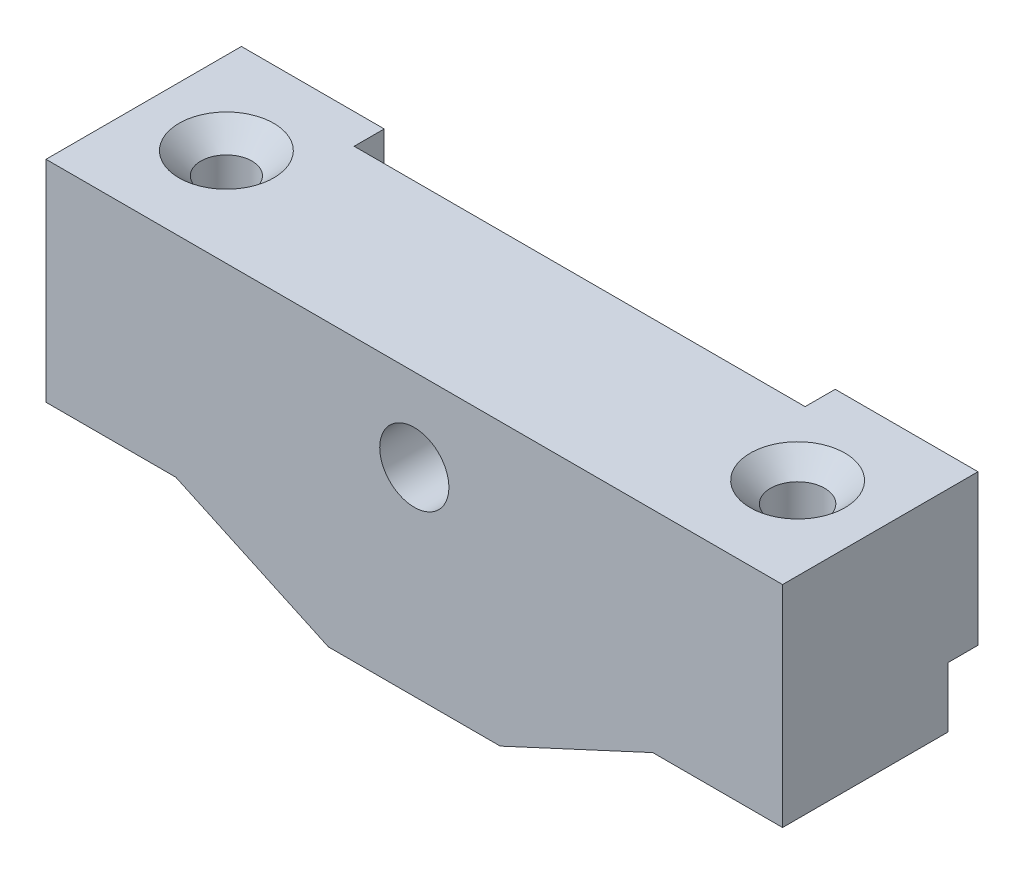
SolidWorks part; units mm, degrees
ref_plane "Front Plane" through (0, 0, 0) normal (0, 0, 1) x (1, 0, 0)
ref_plane "Top Plane" through (0, 0, 0) normal (0, 1, 0) x (1, 0, 0)
ref_plane "Right Plane" through (0, 0, 0) normal (1, 0, 0) x (0, 0, -1)
sketch "Sketch2" plane through (0, 0, 0) normal (0, 0, 1) x (1, 0, 0)
  line L0 (12.9822, 18.1755) -> (23.9822, 18.1755)
  line L1 (23.9822, 18.1755) -> (42.9822, 26.9755)
  line L2 (42.9822, 26.9755) -> (42.9822, 36.9755)
  line L3 (42.9822, 36.9755) -> (-6.0178, 36.9755)
  line L4 (-6.0178, 36.9755) -> (-6.0178, 26.9755)
  line L5 (-6.0178, 26.9755) -> (12.9822, 18.1755)
  line L6 (18.4822, 18.1755) -> (18.4822, 26.9755) construction
  point P10 (18.4822, 36.9755)
  point P11 (18.4822, 18.1755)
  dimension "D1" = 11
  dimension "D2" = 49
  dimension "D3" = 10
  dimension "D4" = 8.8
  dimension "D5" = 10
extrude "Boss-Extrude1" add sketch "Sketch2" along normal blind 14
sketch "Sketch3" plane through (0, 18.1755, 0) normal (0, -1, 0) x (1, 0, 0)
  line L0 (12.9822, 14) -> (23.9822, 0) construction
  circle A0 centre (18.4822, 7) radius 4.125
  dimension "D1" = 8.25
extrude "Cut-Extrude1" cut sketch "Sketch3" against normal blind 8.8
sketch "Sketch4" plane through (0, 36.9755, 0) normal (0, 1, 0) x (1, 0, 0)
  line L0 (-6.0178, -2) -> (42.9822, -2)
  line L1 (-6.0178, -14) -> (-6.0178, 0) construction
  line L2 (42.9822, -14) -> (42.9822, 0) construction
  line L3 (42.9822, -2) -> (42.9822, -16)
  line L4 (42.9822, -16) -> (-6.0178, -16)
  line L5 (-6.0178, -16) -> (-6.0178, -2)
  line L6 (42.9822, 0) -> (-6.0178, 0) construction
  line L7 (42.9822, -14) -> (-6.0178, -14) construction
  dimension "D1" = 2
  dimension "D2" = 2
ref_plane "Plane1" through (0, 0, 7) normal (0, 0, -1) x (-1, 0, 0)
sketch "Sketch8" plane through (0, 18.1755, 0) normal (0, -1, 0) x (1, 0, 0)
  line L0 (18.4822, 7) -> (37.4822, 7) construction
  line L1 (18.4822, 7) -> (18.4822, 15.5986) construction
  circle A0 centre (37.4822, 7) radius 2.7
  circle A1 centre (-0.5178, 7) radius 2.7
  dimension "D2" = 5.4
  dimension "D1" = 19
extrude "Cut-Extrude3" cut sketch "Sketch8" against normal through all
sketch "Sketch11" plane through (0, 18.1755, 0) normal (0, -1, 0) x (1, 0, 0)
  line L0 (-6.0178, 14) -> (-6.0178, 13.5)
  line L1 (-6.0178, 13.5) -> (42.9822, 13.5)
  line L2 (42.9822, 13.5) -> (42.9822, 14)
  line L3 (42.9822, 14) -> (-6.0178, 14)
  line L4 (-6.0178, 0) -> (-6.0178, 0.5)
  line L5 (-6.0178, 0.5) -> (42.9822, 0.5)
  line L6 (42.9822, 0.5) -> (42.9822, 0)
  line L7 (42.9822, 0) -> (-6.0178, 0)
  line L8 (-6.0178, 14) -> (12.9822, 14) construction
  line L9 (-6.0178, 0) -> (12.9822, 0) construction
  line L10 (42.9822, 2) -> (42.9822, 16) construction
  line L11 (42.9822, 14) -> (42.9822, 0) construction
  dimension "D1" = 0.5
extrude "Cut-Extrude6" cut sketch "Sketch11" against normal through all
sketch "Sketch12" plane through (0, 36.9755, 0) normal (0, 1, 0) x (1, 0, 0)
  circle A0 centre (-0.5178, -7) radius 2.7
  circle A1 centre (37.4822, -7) radius 2.7
  circle A2 centre (-0.5178, -7) radius 1.5
  circle A3 centre (-0.5178, -7) radius 2.7 construction
  circle A4 centre (37.4822, -7) radius 1.8
  circle A5 centre (37.4822, -7) radius 2.7 construction
  dimension "D1" = 3
  dimension "D2" = 3.6
extrude "Boss-Extrude2" add sketch "Sketch12" against normal blind 4
sketch "Sketch15" plane through (0, 0, 0.5) normal (0, 0, -1) x (-1, 0, 0)
  line L0 (-33.4822, 22.5755) -> (-33.4822, 36.9755)
  line L1 (-23.9822, 18.1755) -> (-42.9822, 26.9755) construction
  line L2 (-42.9822, 36.9755) -> (6.0178, 36.9755) construction
  line L3 (-33.4822, 22.5755) -> (-23.9822, 18.1755)
  line L4 (-23.9822, 18.1755) -> (-12.9822, 18.1755)
  line L5 (-23.9822, 18.1755) -> (-12.9822, 18.1755) construction
  line L6 (-18.4822, 18.1755) -> (-18.4822, 29.0528) construction
  line L7 (-33.4822, 36.9755) -> (-3.4822, 36.9755)
  line L8 (-3.4822, 22.5755) -> (-12.9822, 18.1755)
  line L9 (-3.4822, 22.5755) -> (-3.4822, 36.9755)
  point P16 (-18.4822, 36.9755)
extrude "Cut-Extrude7" cut sketch "Sketch15" against normal blind 2
sketch "Sketch18" plane through (0, 32.9755, 0) normal (0, -1, 0) x (1, 0, 0)
  circle A0 centre (37.4822, 7) radius 2.7
  circle A1 centre (37.4822, 7) radius 2.4
  circle A2 centre (37.4822, 7) radius 2.7 construction
  circle A4 centre (-0.5178, 7) radius 2.4
  circle A5 centre (-0.5178, 7) radius 2.7
  circle A6 centre (-0.5178, 7) radius 2.7 construction
  dimension "D1" = 4.8
  dimension "D2" = 4.8
extrude "Boss-Extrude3" add sketch "Sketch18" along normal blind 5
sketch "Sketch17" plane through (0, 0, 2.5) normal (0, 0, -1) x (-1, 0, 0)
  line L0 (-18.4822, 18.1755) -> (-18.4822, 36.9755) construction
  line L1 (-23.9822, 18.1755) -> (-12.9822, 18.1755) construction
  line L2 (-3.4822, 36.9755) -> (-33.4822, 36.9755) construction
  line L3 (-24.1981, 18.1755) -> (-24.1981, 18.2755)
  line L4 (-24.1981, 18.2755) -> (-12.7663, 18.2755)
  line L5 (-12.7663, 18.2755) -> (-12.7663, 18.1755)
  line L6 (-12.7663, 18.1755) -> (-24.1981, 18.1755)
  line L7 (-33.4822, 22.5755) -> (-23.9822, 18.1755) construction
  line L8 (-12.9822, 18.1755) -> (-3.4822, 22.5755) construction
  circle A0 centre (-18.4822, 31.4755) radius 2.3
  point P14 (-18.4822, 33.7755)
  dimension "D2" = 4.6
  dimension "D1" = 0.1
  dimension "D3" = 3.2
extrude "Cut-Extrude8" cut sketch "Sketch17" against normal blind 22
sketch "Sketch19" plane through (0, 18.2755, 0) normal (0, -1, 0) x (1, 0, 0)
  line L0 (12.7663, 2.5) -> (24.1981, 2.5)
  line L1 (24.1981, 2.5) -> (24.1981, 13.5)
  line L2 (24.1981, 13.5) -> (12.7663, 13.5)
  line L3 (12.7663, 13.5) -> (12.7663, 2.5)
  point P6 (18.4822, 7)
  dimension "D1" = 6.5
ref_plane "Plane2" through (0, 26.9755, 0) normal (0, -1, 0) x (-1, 0, 0)
sketch "Sketch20" plane through (0, 26.9755, 0) normal (0, -1, 0) x (-1, 0, 0)
  line L0 (-33.4822, -2.5) -> (-42.9822, -2.5)
  line L1 (-42.9822, -13.5) -> (-42.9822, -0.5) construction
  line L2 (-42.9822, -2.5) -> (-42.9822, -13.5)
  line L3 (-42.9822, -13.5) -> (-33.4822, -13.5)
  line L4 (-42.9822, -13.5) -> (-24.1981, -13.5) construction
  line L5 (-33.4822, -13.5) -> (-33.4822, -2.5)
  line L6 (-3.4822, -2.5) -> (6.0178, -2.5)
  line L7 (6.0178, -13.5) -> (6.0178, -0.5) construction
  line L8 (6.0178, -2.5) -> (6.0178, -13.5)
  line L9 (6.0178, -13.5) -> (-3.4822, -13.5)
  line L10 (-12.7663, -13.5) -> (6.0178, -13.5) construction
  line L11 (-3.4822, -13.5) -> (-3.4822, -2.5)
  circle A0 centre (-37.4822, -7) radius 2.7
  circle A1 centre (0.5178, -7) radius 2.55
  dimension "D1" = 5.4
  dimension "D2" = 5.1
extrude "Boss-Extrude4" add sketch "Sketch20" along normal blind 4 and the other way through all
sketch "Sketch21" plane through (0, 22.9755, 0) normal (0, -1, 0) x (1, 0, 0)
  circle A0 centre (-0.5178, 7) radius 2.55
  circle A1 centre (37.4822, 7) radius 2.7
  circle A2 centre (-0.5178, 7) radius 2.55 construction
  dimension "D1" = 5.1
  dimension "D2" = 5.4
extrude "Cut-Extrude9" cut sketch "Sketch21" against normal up to surface (10 mm away) up to face at (37.4822, 32.9755, 8.8)
sketch "Sketch22" plane through (0, 36.9755, 0) normal (0, 1, 0) x (1, 0, 0)
  point P0 (-0.5178, -7)
  point P1 (37.4822, -7)
hole_wizard "CSK for M3 Flat Head Machine Screw1" positions "Sketch22" profile "Sketch23" countersink size "M3" standard "ANSI Metric" end condition through all
sketch "Sketch23" plane through (-0.5178, 36.9755, 7) normal (1, 0, 0) x (0, 0, 1)
  line L0 (0, 0) -> (0, 18.7)
  line L1 (0, 18.7) -> (1.7, 18.7)
  line L2 (1.7, 18.7) -> (1.7, 1.45)
  line L3 (1.7, 1.45) -> (3.15, 0)
  line L5 (3.15, 0) -> (0, 0)
  line L6 (-1.7, 1.45) -> (-3.15, 0) construction
  line L11 (0, -6.35) -> (0, 107.95) construction
  dimension "Thru Hole Dia." = 3.4
  dimension "Thru Hole Depth" = 18.7
  dimension "Near C'Sink Dia." = 6.3
  dimension "Near C'Sink Angle" = 90
